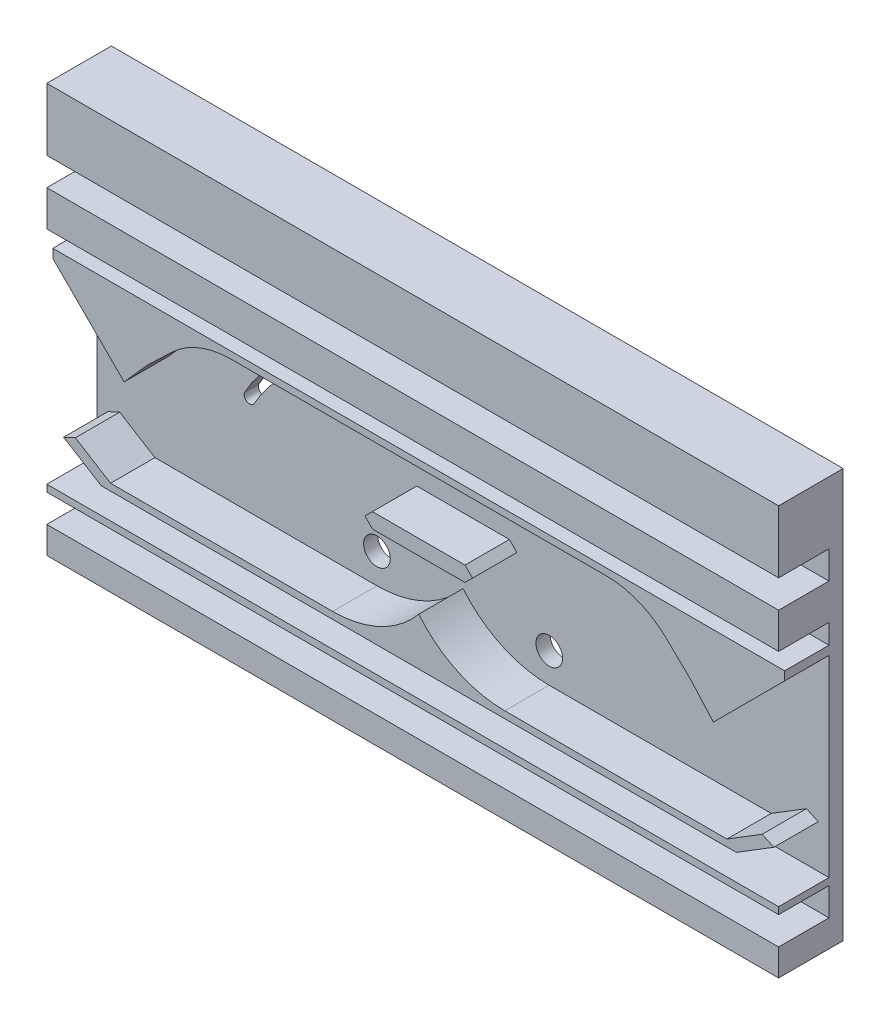
SolidWorks part; units mm, degrees
ref_plane "Front Plane" through (0, 0, 0) normal (0, 0, 1) x (1, 0, 0)
ref_plane "Top Plane" through (0, 0, 0) normal (0, 1, 0) x (1, 0, 0)
ref_plane "Right Plane" through (0, 0, 0) normal (1, 0, 0) x (0, 0, -1)
sketch "Sketch1" plane through (0, 0, 0) normal (0, 0, 1) x (1, 0, 0)
  line L0 (381, 92.3925) -> (367.3475, 92.3925)
  line L1 (381, 110.49) -> (325.6172, 110.49)
  line L2 (279.6982, 67.437) -> (290.0904, 61.0235)
  line L3 (365.125, 90.17) -> (367.3475, 92.3925)
  line L4 (365.125, 90.17) -> (367.3475, 87.9475)
  line L5 (294.0823, 88.9) -> (273.05, 109.9323)
  line L6 (287.3375, 58.9915) -> (276.225, 65.8495)
  line L7 (276.225, 65.8495) -> (279.6982, 67.437)
  line L8 (300.99, 96.647) -> (294.0823, 88.9)
  line L9 (300.99, 96.647) -> (308.0122, 103.3992)
  line L10 (301.3075, 46.99) -> (300.7868, 46.99)
  line L11 (488.95, 34.925) -> (488.95, 155.575)
  line L12 (381, 34.925) -> (488.95, 34.925)
  line L13 (381, 42.8625) -> (488.95, 42.8625)
  line L14 (482.3018, 67.437) -> (471.9096, 61.0235)
  line L15 (396.875, 90.17) -> (394.6525, 92.3925)
  line L16 (396.875, 90.17) -> (394.6525, 87.9475)
  line L17 (467.9177, 88.9) -> (488.95, 109.9323)
  line L18 (273.05, 155.575) -> (381, 155.575)
  line L19 (381, 34.925) -> (273.05, 34.925)
  line L20 (273.05, 34.925) -> (273.05, 155.575)
  line L21 (381, 42.8625) -> (273.05, 42.8625)
  line L22 (273.05, 51.1175) -> (381, 51.1175)
  line L23 (381, 137.16) -> (273.05, 137.16)
  line L24 (273.05, 128.905) -> (381, 128.905)
  line L25 (287.3375, 58.9915) -> (381, 58.9915)
  line L26 (290.0904, 61.0235) -> (355.6, 61.0235)
  line L27 (367.3475, 87.9475) -> (381, 87.9475)
  line L28 (365.125, 90.17) -> (367.3475, 87.9475)
  line L29 (367.3475, 92.3925) -> (365.125, 90.17)
  line L30 (488.95, 118.364) -> (273.05, 118.364)
  line L31 (488.95, 112.522) -> (273.05, 112.522)
  line L32 (474.6625, 58.9915) -> (485.775, 65.8495)
  line L33 (485.775, 65.8495) -> (482.3018, 67.437)
  line L34 (461.01, 96.647) -> (467.9177, 88.9)
  line L35 (461.01, 96.647) -> (453.9878, 103.3992)
  line L36 (488.95, 155.575) -> (381, 155.575)
  line L37 (488.95, 51.1175) -> (381, 51.1175)
  line L38 (381, 137.16) -> (488.95, 137.16)
  line L39 (488.95, 128.905) -> (381, 128.905)
  line L40 (474.6625, 58.9915) -> (381, 58.9915)
  line L41 (471.9096, 61.0235) -> (406.4, 61.0235)
  line L42 (394.6525, 87.9475) -> (381, 87.9475)
  line L43 (396.875, 90.17) -> (394.6525, 87.9475)
  line L44 (394.6525, 92.3925) -> (396.875, 90.17)
  line L45 (381, 92.3925) -> (394.6525, 92.3925)
  line L46 (381, 110.49) -> (436.3828, 110.49)
  line L47 (460.6925, 46.99) -> (461.2132, 46.99)
  arc A0 (355.6, 61.0235) -> (381, 69.85) centre (355.6, 101.9835) ccw
  arc A1 (325.6172, 110.49) -> (308.0122, 103.3992) centre (325.6172, 85.09) ccw
  circle A2 centre (381, 46.99) radius 1.1303
  circle A3 centre (301.0471, 46.99) radius 1.1303
  circle A4 centre (460.9528, 46.99) radius 1.1303
  circle A5 centre (355.5825, 69.8475) radius 3.937
  arc A6 (316.6215, 91.064) -> (319.4098, 89.5456) centre (318.0156, 90.3048) ccw
  arc A7 (326.2581, 98.7555) -> (323.852, 100.8152) centre (325.1295, 99.8722) ccw
  arc A8 (323.852, 100.8152) -> (316.6215, 91.064) centre (354.9876, 70.1715) ccw
  arc A9 (326.2581, 98.7555) -> (319.4098, 89.5456) centre (355.3412, 69.9789) ccw
  arc A10 (381, 69.85) -> (406.4, 61.0235) centre (406.4, 101.9835) ccw
  arc A11 (453.9878, 103.3992) -> (436.3828, 110.49) centre (436.3828, 85.09) ccw
  circle A12 centre (406.4175, 69.8475) radius 3.937
  arc A13 (442.5902, 89.5456) -> (445.3785, 91.064) centre (443.9844, 90.3048) ccw
  arc A14 (438.148, 100.8152) -> (435.7419, 98.7555) centre (436.8705, 99.8722) ccw
  arc A15 (445.3785, 91.064) -> (438.148, 100.8152) centre (407.0124, 70.1715) ccw
  arc A16 (442.5902, 89.5456) -> (435.7419, 98.7555) centre (406.6588, 69.9789) ccw
sketch "Sketch3" plane through (0, 0, 0) normal (0, 0, 1) x (1, 0, 0)
  line L1 (273.05, 155.575) -> (488.95, 155.575)
  line L2 (273.05, 155.575) -> (273.05, 34.925)
  line L3 (273.05, 34.925) -> (488.95, 34.925)
  line L4 (488.95, 155.575) -> (488.95, 34.925)
extrude "Extrude1" add sketch "Sketch3" along normal blind 4.191
sketch "Sketch4" plane through (0, 0, 0) normal (0, 0, 1) x (1, 0, 0)
  line L0 (488.95, 34.925) -> (488.95, 155.575) construction
  line L1 (273.05, 155.575) -> (488.95, 155.575)
  line L2 (273.05, 155.575) -> (273.05, 137.16)
  line L3 (273.05, 137.16) -> (488.95, 137.16)
  line L4 (488.95, 155.575) -> (488.95, 137.16)
  line L5 (273.05, 128.905) -> (488.95, 128.905)
  line L6 (273.05, 128.905) -> (273.05, 118.364)
  line L7 (273.05, 118.364) -> (488.95, 118.364)
  line L8 (488.95, 128.905) -> (488.95, 118.364)
  line L9 (273.05, 34.925) -> (488.95, 34.925)
  line L10 (273.05, 34.925) -> (273.05, 42.8625)
  line L11 (273.05, 42.8625) -> (488.95, 42.8625)
  line L12 (488.95, 34.925) -> (488.95, 42.8625)
  line L13 (273.05, 51.1175) -> (488.95, 51.1175)
  line L14 (273.05, 51.1175) -> (273.05, 53.1495)
  line L15 (273.05, 53.1495) -> (488.95, 53.1495)
  line L16 (488.95, 51.1175) -> (488.95, 53.1495)
extrude "Extrude2" add sketch "Sketch4" along normal blind 19.05
sketch "Sketch5" plane through (0, 0, 0) normal (0, 0, 1) x (1, 0, 0)
  line L0 (381, 58.9915) -> (287.3375, 58.9915)
  line L1 (287.3375, 58.9915) -> (276.225, 65.8495)
  line L2 (287.3375, 58.9915) -> (276.225, 65.8495) construction
  line L3 (279.6982, 67.437) -> (276.225, 65.8495)
  line L4 (279.6982, 67.437) -> (290.0904, 61.0235)
  line L5 (290.0904, 61.0235) -> (355.6, 61.0235)
  line L6 (381, 58.9915) -> (474.6625, 58.9915)
  line L7 (474.6625, 58.9915) -> (485.775, 65.8495)
  line L8 (485.775, 65.8495) -> (482.3018, 67.437)
  line L9 (482.3018, 67.437) -> (471.9096, 61.0235)
  line L10 (471.9096, 61.0235) -> (406.4, 61.0235)
  line L11 (381, 87.9475) -> (367.3475, 87.9475)
  line L12 (367.3475, 87.9475) -> (365.125, 90.17)
  line L13 (365.125, 90.17) -> (367.3475, 92.3925)
  line L14 (367.3475, 92.3925) -> (381, 92.3925)
  line L15 (381, 92.3925) -> (394.6525, 92.3925)
  line L16 (394.6525, 92.3925) -> (396.875, 90.17)
  line L17 (396.875, 90.17) -> (394.6525, 87.9475)
  line L18 (394.6525, 87.9475) -> (381, 87.9475)
  line L19 (436.3828, 110.49) -> (325.6172, 110.49)
  line L20 (308.0122, 103.3992) -> (300.99, 96.647)
  line L21 (300.99, 96.647) -> (294.0823, 88.9)
  line L22 (294.0823, 88.9) -> (273.05, 109.9323)
  line L23 (273.05, 109.9323) -> (273.05, 112.522)
  line L24 (273.05, 112.522) -> (488.95, 112.522)
  line L25 (488.95, 112.522) -> (488.95, 109.9323)
  line L26 (488.95, 109.9323) -> (467.9177, 88.9)
  line L27 (467.9177, 88.9) -> (461.01, 96.647)
  line L28 (461.01, 96.647) -> (453.9878, 103.3992)
  line L29 (381, 69.85) -> (381, 73.025) construction
  arc A0 (355.6, 61.0235) -> (381, 69.85) centre (355.6, 101.9835) ccw construction
  arc A1 (406.4, 61.0235) -> (381, 69.85) centre (406.4, 101.9835) cw construction
  arc A2 (325.6172, 110.49) -> (308.0122, 103.3992) centre (325.6172, 85.09) ccw
  arc A3 (453.9878, 103.3992) -> (436.3828, 110.49) centre (436.3828, 85.09) ccw
  arc A4 (355.6, 61.0235) -> (381, 73.025) centre (355.6, 93.9026) ccw
  arc A5 (406.4, 61.0235) -> (381, 73.025) centre (406.4, 93.9026) cw
extrude "Extrude3" add sketch "Sketch5" along normal blind 17.272
sketch "Sketch8" plane through (0, 0, 0) normal (0, 0, 1) x (1, 0, 0)
  arc A0 (319.4098, 89.5456) -> (326.2581, 98.7555) centre (355.3412, 69.9789) cw
  arc A3 (316.6215, 91.064) -> (323.852, 100.8152) centre (354.9876, 70.1715) cw
  arc A4 (323.852, 100.8152) -> (326.2581, 98.7555) centre (325.1295, 99.8722) cw
  arc A5 (319.4098, 89.5456) -> (316.6215, 91.064) centre (318.0156, 90.3048) cw
  arc A6 (438.148, 100.8152) -> (445.3785, 91.064) centre (407.0124, 70.1715) cw
  arc A7 (435.7419, 98.7555) -> (442.5902, 89.5456) centre (406.6588, 69.9789) cw
  arc A8 (445.3785, 91.064) -> (442.5902, 89.5456) centre (443.9844, 90.3048) cw
  arc A9 (435.7419, 98.7555) -> (438.148, 100.8152) centre (436.8705, 99.8722) cw
  circle A10 centre (355.5825, 69.8475) radius 3.937
  circle A11 centre (406.4175, 69.8475) radius 3.937
  circle A12 centre (381, 46.99) radius 1.1303
  circle A13 centre (460.9528, 46.99) radius 1.1303
  circle A14 centre (301.0471, 46.99) radius 1.1303
extrude "Cut-Extrude1" cut sketch "Sketch8" along normal up to surface (19.05 mm away) up to face at (381, 146.3675, 19.05)
